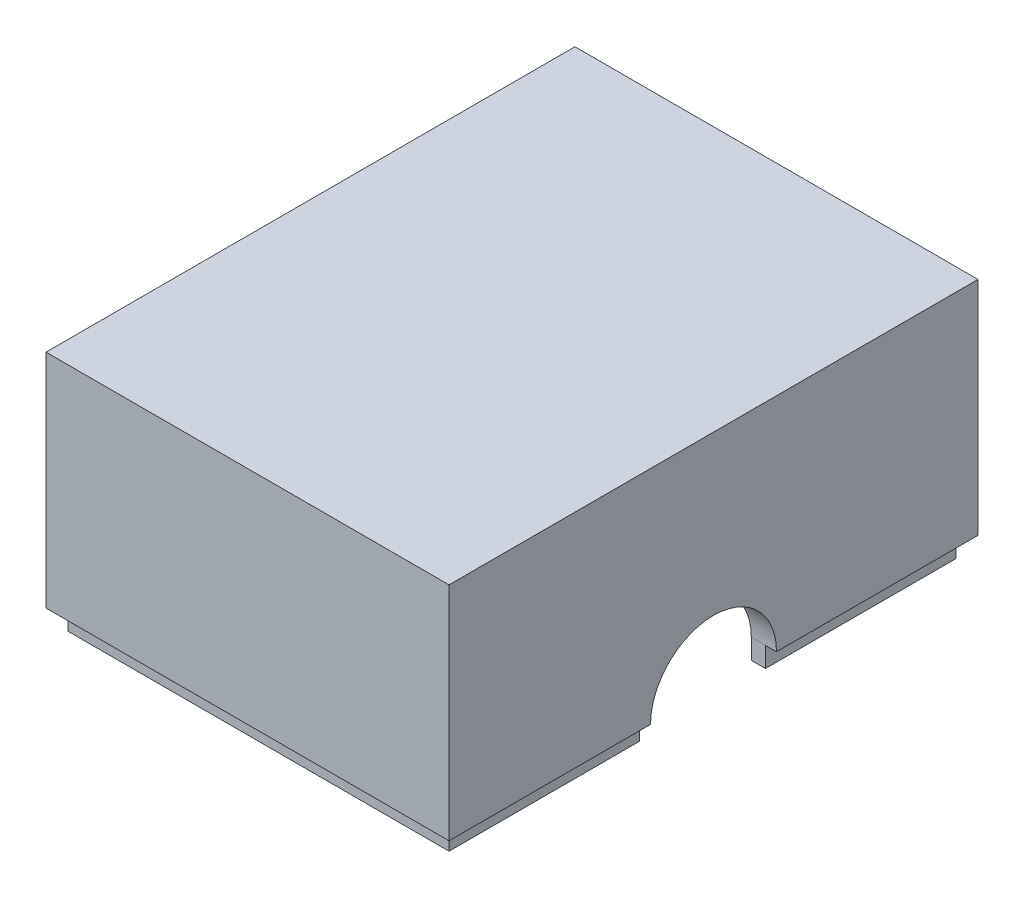
SolidWorks part; units mm, degrees
ref_plane "Front Plane" through (0, 0, 0) normal (0, 0, 1) x (1, 0, 0)
ref_plane "Top Plane" through (0, 0, 0) normal (0, 1, 0) x (1, 0, 0)
ref_plane "Right Plane" through (0, 0, 0) normal (1, 0, 0) x (0, 0, -1)
sketch "Sketch1" plane through (0, 0, 0) normal (0, 1, 0) x (1, 0, 0)
  line L5 (-40, -52.5) -> (40, -52.5)
  line L6 (-40, -52.5) -> (-40, 52.5)
  line L7 (-40, 52.5) -> (40, 52.5)
  line L8 (40, -52.5) -> (40, 52.5)
  line L9 (-40, -52.5) -> (40, 52.5) construction
  line L10 (-40, 52.5) -> (40, -52.5) construction
  point P0 (0, 0)
  dimension "D1" = 80
  dimension "D2" = 105
extrude "Boss-Extrude1" add sketch "Sketch1" along normal blind 48
sketch "Sketch3" plane through (0, 0, 0) normal (0, -1, 0) x (1, 0, 0)
  line L1 (-35, -47.5) -> (35, -47.5)
  line L2 (-35, -47.5) -> (-35, 47.5)
  line L3 (-35, 47.5) -> (35, 47.5)
  line L4 (35, -47.5) -> (35, 47.5)
  line L5 (-35, -47.5) -> (35, 47.5) construction
  line L6 (-35, 47.5) -> (35, -47.5) construction
  point P0 (0, 0)
  dimension "D1" = 70
  dimension "D2" = 95
extrude "Cut-Extrude1" cut sketch "Sketch3" against normal blind 45
sketch "Sketch4" plane through (0, 0, 0) normal (0, -1, 0) x (1, 0, 0)
  line L0 (40, -52.5) -> (-40, -52.5) construction
  line L1 (40, 52.5) -> (40, -52.5) construction
  line L2 (-40, 52.5) -> (40, 52.5) construction
  line L3 (-40, -52.5) -> (-40, 52.5) construction
  line L4 (40, -52.5) -> (-40, -52.5)
  line L5 (40, 52.5) -> (40, -52.5)
  line L6 (-40, 52.5) -> (40, 52.5)
  line L7 (-40, -52.5) -> (-40, 52.5)
  line L8 (37.8, -50.3) -> (-37.8, -50.3)
  line L9 (-37.8, -50.3) -> (-37.8, 50.3)
  line L10 (-37.8, 50.3) -> (37.8, 50.3)
  line L11 (37.8, 50.3) -> (37.8, -50.3)
  dimension "D1" = 2.2
extrude "Cut-Extrude2" cut sketch "Sketch4" against normal blind 4
sketch "Sketch5" plane through (40, 0, 0) normal (1, 0, 0) x (0, 0, -1)
  line L0 (0, 62.8381) -> (0, -5.7241) construction
  line L2 (52.5, 4) -> (-52.5, 4) construction
  line L4 (-12.5, 4) -> (-12.5, -5.5)
  line L5 (12.5, 4) -> (12.5, -5.5)
  line L6 (-12.5, -5.5) -> (12.5, -5.5)
  line L7 (-52.5, 48) -> (52.5, 48) construction
  arc A0 (12.5, 4) -> (-12.5, 4) centre (0, 4) ccw
  point P14 (0, 48)
  dimension "D1" = 12.5
  dimension "D2" = 9.5
extrude "Cut-Extrude3" cut sketch "Sketch5" against normal through all
